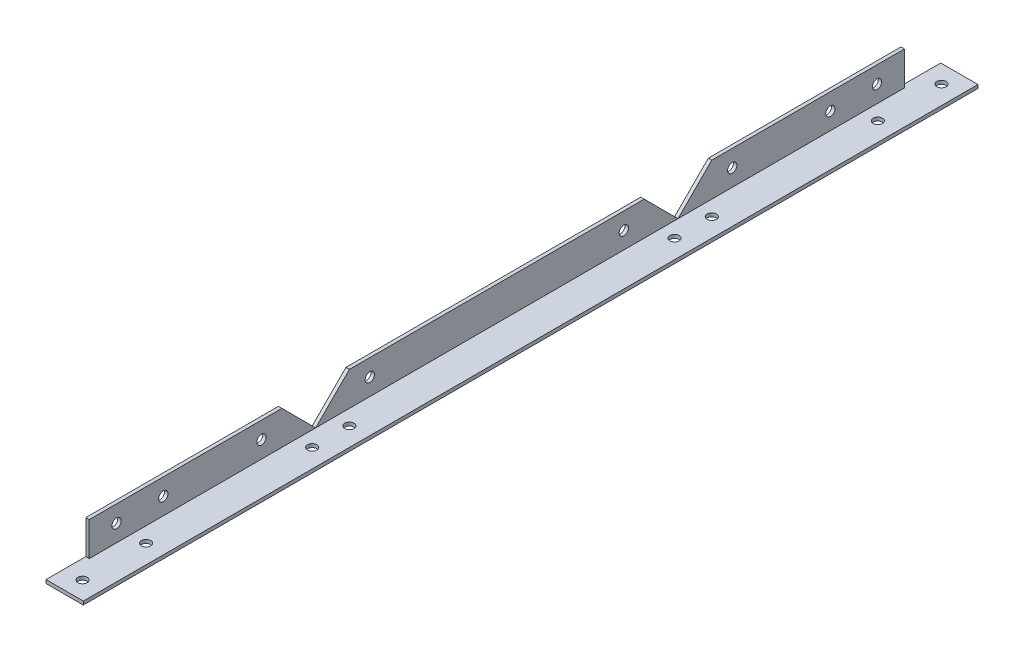
SolidWorks part; units mm, degrees
ref_plane "Front Plane" through (0, 0, 0) normal (0, 0, 1) x (1, 0, 0)
ref_plane "Top Plane" through (0, 0, 0) normal (0, 1, 0) x (1, 0, 0)
ref_plane "Right Plane" through (0, 0, 0) normal (1, 0, 0) x (0, 0, -1)
sketch "Sketch1" plane through (0, 0, 0) normal (0, 0, 1) x (1, 0, 0)
  line L0 (0, 0) -> (0, 17.272)
  line L1 (0, 17.272) -> (-1.778, 17.272)
  line L2 (-1.778, 17.272) -> (-1.778, -1.778)
  line L3 (-1.778, -1.778) -> (17.272, -1.778)
  line L4 (17.272, -1.778) -> (17.272, 0)
  line L5 (17.272, 0) -> (0, 0)
  dimension "D1" = 1.778
  dimension "D2" = 1.778
  dimension "D3" = 19.05
  dimension "D4" = 19.05
extrude "Boss-Extrude1" add sketch "Sketch1" along normal blind 208.28
sketch "Sketch2" plane through (0, 0, 0) normal (1, 0, 0) x (0, 0, -1)
  line L0 (-92.583, 0) -> (-109.855, 17.272)
  line L1 (-208.28, 0) -> (0, 0) construction
  line L2 (-208.28, 17.272) -> (0, 17.272) construction
  line L3 (-109.855, 17.272) -> (-75.311, 17.272)
  line L4 (-75.311, 17.272) -> (-92.583, 0)
  line L5 (-208.28, 0) -> (0, 0) construction
  line L6 (-208.28, 0) -> (-208.28, 17.272) construction
  circle A0 centre (-194.31, 8.636) radius 2.3813
  circle A1 centre (-170.434, 8.636) radius 2.3813
  circle A2 centre (-120.269, 8.636) radius 2.3813
  circle A3 centre (-64.897, 8.636) radius 2.3813
  dimension "D8" = 4.7625
  dimension "D9" = 4.7625
  dimension "D10" = 4.7625
  dimension "D11" = 4.7625
  dimension "D13" = 23.876
  dimension "D14" = 10.414
  dimension "D15" = 10.414
  dimension "D1" = 45
  dimension "D2" = 45
  dimension "D3" = 115.697
  dimension "D4" = 8.636
  dimension "D5" = 8.636
  dimension "D6" = 8.636
  dimension "D7" = 8.636
  dimension "D12" = 13.97
extrude "Cut-Extrude1" cut sketch "Sketch2" against normal up to surface (1.778 mm away) up to face at (-1.778, 7.747, 104.14)
sketch "Sketch3" plane through (0, 0, 208.28) normal (0, 0, 1) x (1, 0, 0)
  line L1 (-1.778, -1.778) -> (17.272, -1.778)
  line L2 (-1.778, -1.778) -> (-1.778, 0)
  line L3 (-1.778, 0) -> (17.272, 0)
  line L4 (17.272, -1.778) -> (17.272, 0)
extrude "Boss-Extrude2" add sketch "Sketch3" along normal blind 20.32
sketch "Sketch4" plane through (0, 0, 0) normal (0, 1, 0) x (1, 0, 0)
  line L0 (17.272, -228.6) -> (-1.778, -228.6) construction
  line L1 (-1.778, -228.6) -> (-1.778, -208.28) construction
  line L2 (0, -92.583) -> (0, 0) construction
  line L3 (0, -208.28) -> (0, -92.583) construction
  circle A0 centre (7.747, -219.456) radius 2.3812
  circle A1 centre (7.747, -83.058) radius 2.3813
  circle A2 centre (7.747, -102.108) radius 2.3812
  circle A3 centre (7.747, -186.944) radius 2.3812
  dimension "D1" = 9.144
  dimension "D2" = 4.7625
  dimension "D4" = 4.7625
  dimension "D7" = 4.7625
  dimension "D10" = 41.656
  dimension "D11" = 4.7625
  dimension "D12" = 7.747
  dimension "D3" = 9.525
  dimension "D5" = 9.525
  dimension "D6" = 7.747
  dimension "D8" = 9.525
  dimension "D9" = 7.747
extrude "Cut-Extrude2" cut sketch "Sketch4" against normal up to surface (1.778 mm away) up to face at (7.747, -1.778, 114.3)
mirror "Mirror3" about plane through (0, 0, 0) normal (0, 0, -1) of "Cut-Extrude2", "Boss-Extrude2", "Cut-Extrude1", "Boss-Extrude1"
